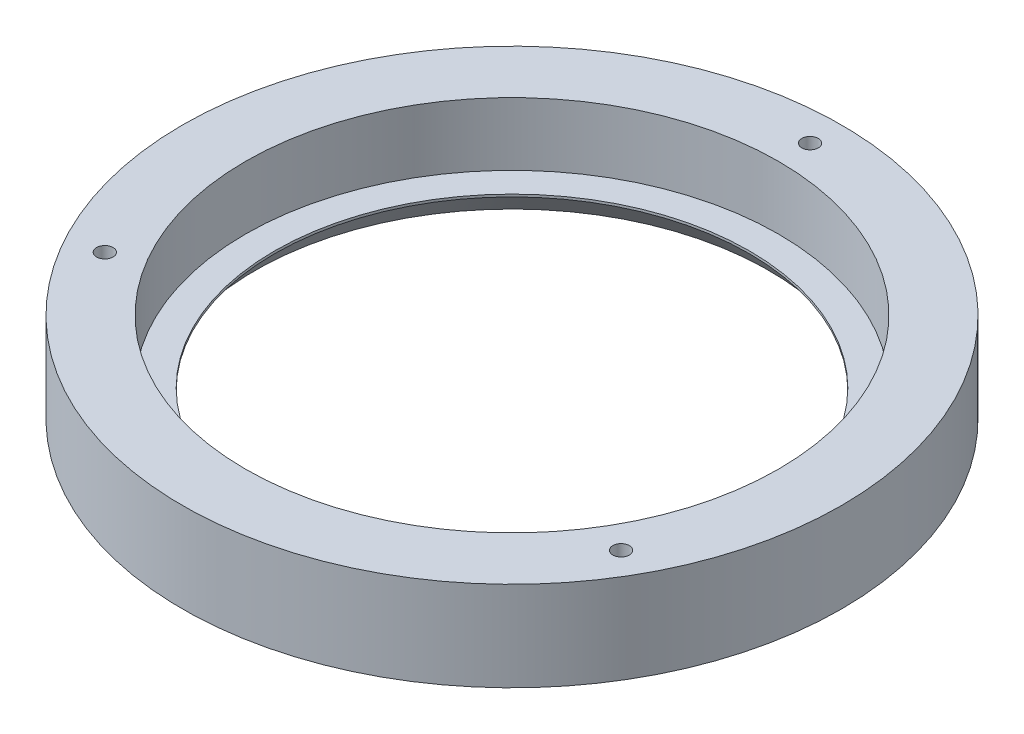
SolidWorks part; units mm, degrees
ref_plane "Front Plane" through (0, 0, 0) normal (0, 0, 1) x (1, 0, 0)
ref_plane "Top Plane" through (0, 0, 0) normal (0, 1, 0) x (1, 0, 0)
ref_plane "Right Plane" through (0, 0, 0) normal (1, 0, 0) x (0, 0, -1)
sketch "Sketch2" plane through (0, 0, 0) normal (0, 0, 1) x (1, 0, 0)
  line L0 (0, -18.5) -> (0, 18.5) construction
  line L1 (53, 0) -> (68, 0)
  line L2 (68, 0) -> (68, 18.5)
  line L3 (68, 18.5) -> (55, 18.5)
  line L4 (55, 18.5) -> (55, 5.5)
  line L5 (55, 5.5) -> (49, 5.5)
  line L7 (49, 5.5) -> (49, 5)
  line L8 (49, 5) -> (53, 0)
  point P3 (0, 0)
  dimension "D1" = 15
  dimension "D2" = 0.5
  dimension "D3" = 55
  dimension "D4" = 6
  dimension "D5" = 13
  dimension "D6" = 68
  dimension "D7" = 5.5
revolve "Revolve1" add sketch "Sketch2" angle 360 about L0
sketch "Sketch3" plane through (0, 18.5, 0) normal (0, 1, 0) x (1, 0, 0)
  circle A0 centre (0, 61.5) radius 1.7
  dimension "D1" = 3.4
  dimension "D2" = 61.5
extrude "Cut-Extrude1" cut sketch "Sketch3" against normal through all
pattern_circular "CirPattern1" count 3 over 360 about axis through (0, 0, 0) along (0, 1, 0) of "Cut-Extrude1"
sketch "Sketch4" plane through (0, 0, 0) normal (0, -1, 0) x (1, 0, 0)
  line L0 (-56.6106, 30.75) -> (-49.9106, 30.75) construction
  line L1 (-51.5856, 27.8488) -> (-54.9356, 33.6512) construction
  line L2 (-54.9356, 33.6512) -> (-56.6106, 30.75)
  line L3 (-54.9356, 27.8488) -> (-51.5856, 33.6512) construction
  line L4 (-56.6106, 30.75) -> (-54.9356, 27.8488)
  line L5 (-54.9356, 27.8488) -> (-51.5856, 27.8488)
  line L6 (-51.5856, 27.8488) -> (-49.9106, 30.75)
  line L7 (-49.9106, 30.75) -> (-51.5856, 33.6512)
  line L8 (-51.5856, 33.6512) -> (-54.9356, 33.6512)
  circle A0 centre (-53.2606, 30.75) radius 3.35 construction
  dimension "D1" = 6.7
  dimension "D2" = 60
  dimension "D3" = 60
extrude "Cut-Extrude2" cut sketch "Sketch4" against normal blind 3
pattern_circular "CirPattern2" count 3 over 360 about axis through (0, 0, 0) along (0, 1, 0) of "Cut-Extrude2"
equation "\"D2@Sketch3\"=(((136-110)/2) + 110)/2"
